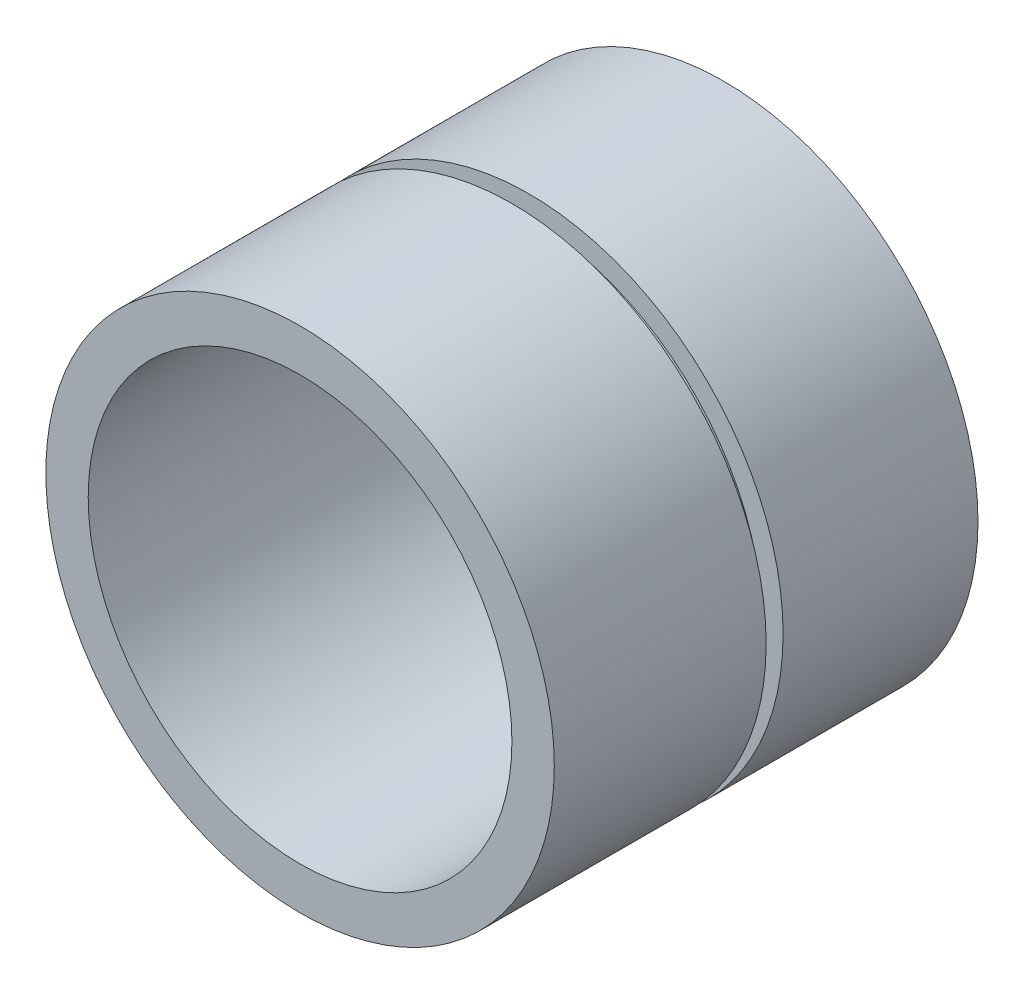
SolidWorks part; units mm, degrees
material "镀铬不锈钢"
ref_plane "前视基准面" through (0, 0, 0) normal (0, 0, 1) x (1, 0, 0)
ref_plane "上视基准面" through (0, 0, 0) normal (0, 1, 0) x (1, 0, 0)
ref_plane "右视基准面" through (0, 0, 0) normal (1, 0, 0) x (0, 0, -1)
other "Configuration Table"
sketch "草图1" plane through (0, 0, 0) normal (0, 0, 1) x (1, 0, 0)
  circle A0 centre (0, 0) radius 2.5
  circle A1 centre (0, 0) radius 3
extrude "凸台-拉伸1" add sketch "草图1" along normal blind 5 contours A1 A0
sketch "草图2" plane through (0, 0, 0) normal (0, 0, -1) x (-1, 0, 0)
  circle A0 centre (0, 0) radius 2.5
extrude "切除-拉伸1" cut sketch "草图2" against normal blind 5
ref_plane "基准面1" through (0, 0, 2.5) normal (0, 0, 1) x (1, 0, 0)
sketch "草图3" plane through (0, 0, 2.5) normal (0, 0, 1) x (1, 0, 0)
  circle A0 centre (0, 0) radius 2.75
  circle A1 centre (0, 0) radius 3
extrude "切除-拉伸2" cut sketch "草图3" against normal blind 0.2 contours A1 | A0
